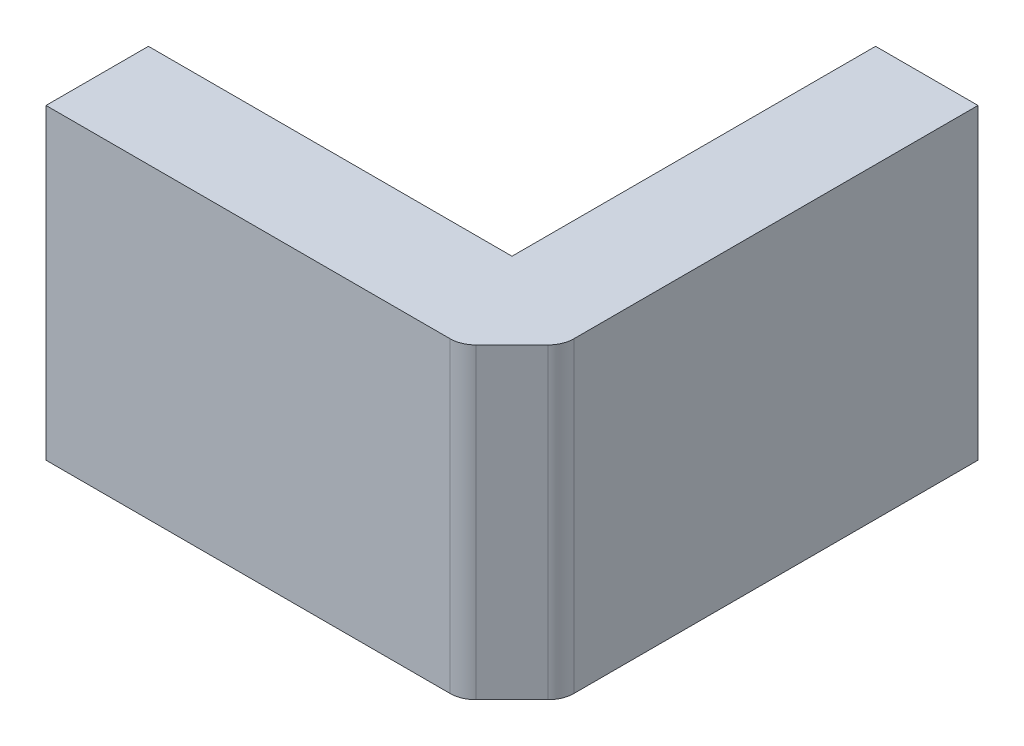
SolidWorks part; units mm, degrees
material "ABS"
ref_plane "Alzado" through (0, 0, 0) normal (0, 0, 1) x (1, 0, 0)
ref_plane "Planta" through (0, 0, 0) normal (0, 1, 0) x (1, 0, 0)
ref_plane "Vista lateral" through (0, 0, 0) normal (1, 0, 0) x (0, 0, -1)
sketch "Sketch1" plane through (0, 0, 0) normal (0, 1, 0) x (1, 0, 0)
  line L0 (25.5, 45.5) -> (25.5, -25.5)
  line L1 (-45.5, -45.5) -> (45.5, -45.5)
  line L2 (-45.5, -45.5) -> (-45.5, 45.5) construction
  line L3 (-45.5, 45.5) -> (45.5, 45.5) construction
  line L4 (45.5, -45.5) -> (45.5, 45.5)
  line L5 (-45.5, -45.5) -> (45.5, 45.5) construction
  line L6 (-45.5, 45.5) -> (45.5, -45.5) construction
  line L7 (25.5, -25.5) -> (-45.5, -25.5)
  line L8 (-45.5, -25.5) -> (-45.5, -45.5)
  line L9 (25.5, 45.5) -> (45.5, 45.5)
  point P0 (0, 0)
  dimension "D1" = 71
  dimension "D3" = 20
extrude "Boss-Extrude1" add sketch "Sketch1" along normal blind 60
chamfer "Chamfer1" distance 10 angle 45 1 edges at (45.5, 30, 45.5)
fillet "Fillet1" radius 5 2 edges at (45.5, 30, 35.5) (35.5, 30, 45.5)
